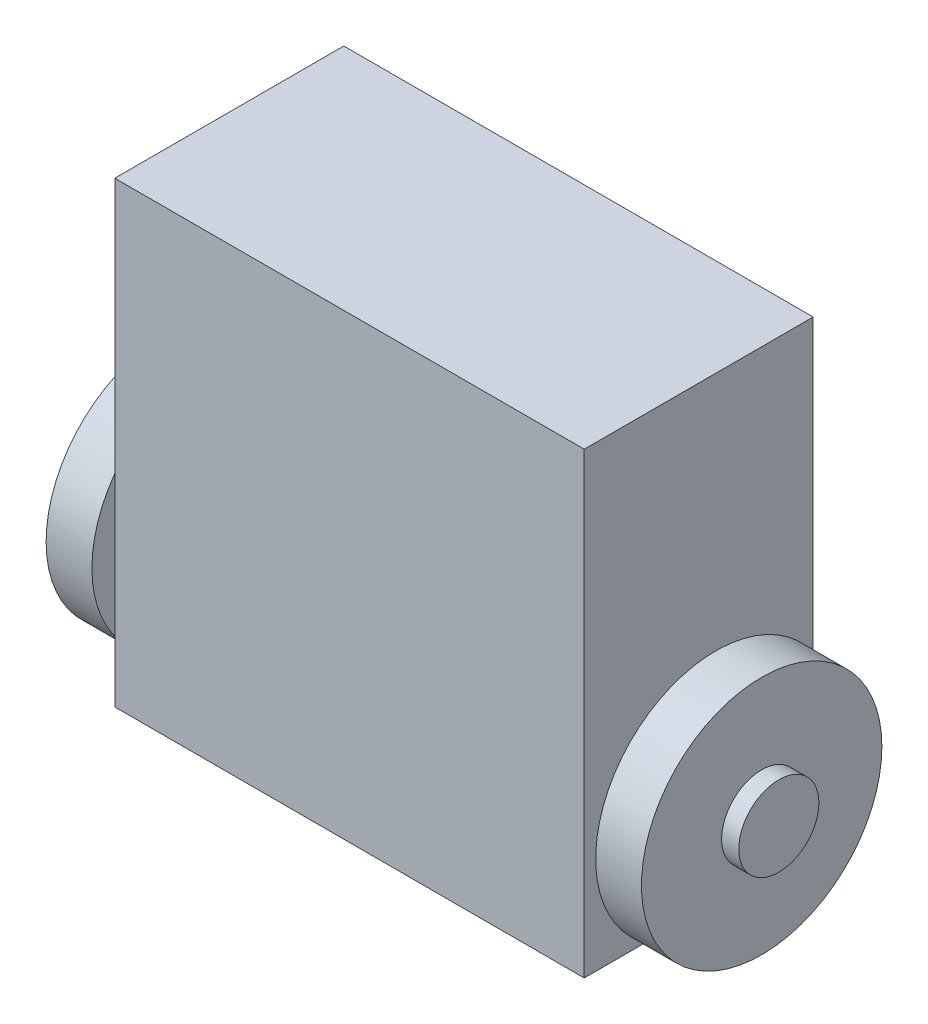
SolidWorks part; units mm, degrees
ref_plane "Alzado" through (0, 0, 0) normal (0, 0, 1) x (1, 0, 0)
ref_plane "Planta" through (0, 0, 0) normal (0, 1, 0) x (1, 0, 0)
ref_plane "Vista lateral" through (0, 0, 0) normal (1, 0, 0) x (0, 0, -1)
sketch "Croquis1" plane through (0, 0, 0) normal (0, 0, 1) x (1, 0, 0)
  line L1 (-20.5, -20) -> (20.5, -20)
  line L2 (-20.5, -20) -> (-20.5, 20)
  line L3 (-20.5, 20) -> (20.5, 20)
  line L4 (20.5, -20) -> (20.5, 20)
  line L5 (-20.5, -20) -> (20.5, 20) construction
  line L6 (-20.5, 20) -> (20.5, -20) construction
  point P0 (0, 0)
  dimension "D1" = 41
  dimension "D2" = 40
extrude "Saliente-Extruir1" add sketch "Croquis1" along normal blind 20
sketch "Croquis2" plane through (20.5, 0, 0) normal (1, 0, 0) x (0, 0, -1)
  line L0 (-10, -20) -> (-10, -10) construction
  line L1 (-20, -20) -> (0, -20) construction
  circle A0 centre (-10, -10) radius 3.5
  dimension "D2" = 7
  dimension "D1" = 10
extrude "Saliente-Extruir2" add sketch "Croquis2" along normal blind 1.5
sketch "Croquis3" plane through (-20.5, 0, 0) normal (-1, 0, 0) x (0, 0, 1)
  circle A0 centre (10, -10) radius 3.5
extrude "Saliente-Extruir3" add sketch "Croquis3" along normal blind 1.5
sketch "Croquis4" plane through (22, 0, 0) normal (1, 0, 0) x (0, 0, -1)
  circle A0 centre (-10, -10) radius 10.5
  dimension "D1" = 21
extrude "Saliente-Extruir4" add sketch "Croquis4" along normal blind 4
sketch "Croquis5" plane through (-22, 0, 0) normal (-1, 0, 0) x (0, 0, 1)
  circle A0 centre (10, -10) radius 10.5
extrude "Saliente-Extruir5" add sketch "Croquis5" along normal blind 4
sketch "Croquis8" plane through (-26, 0, 0) normal (-1, 0, 0) x (0, 0, 1)
  circle A0 centre (10, -10) radius 3.5
  dimension "D1" = 7
extrude "Saliente-Extruir8" add sketch "Croquis8" along normal blind 1.5
sketch "Croquis9" plane through (26, 0, 0) normal (1, 0, 0) x (0, 0, -1)
  circle A0 centre (-10, -10) radius 3.5
  dimension "D1" = 7
extrude "Saliente-Extruir9" add sketch "Croquis9" along normal blind 1.5
